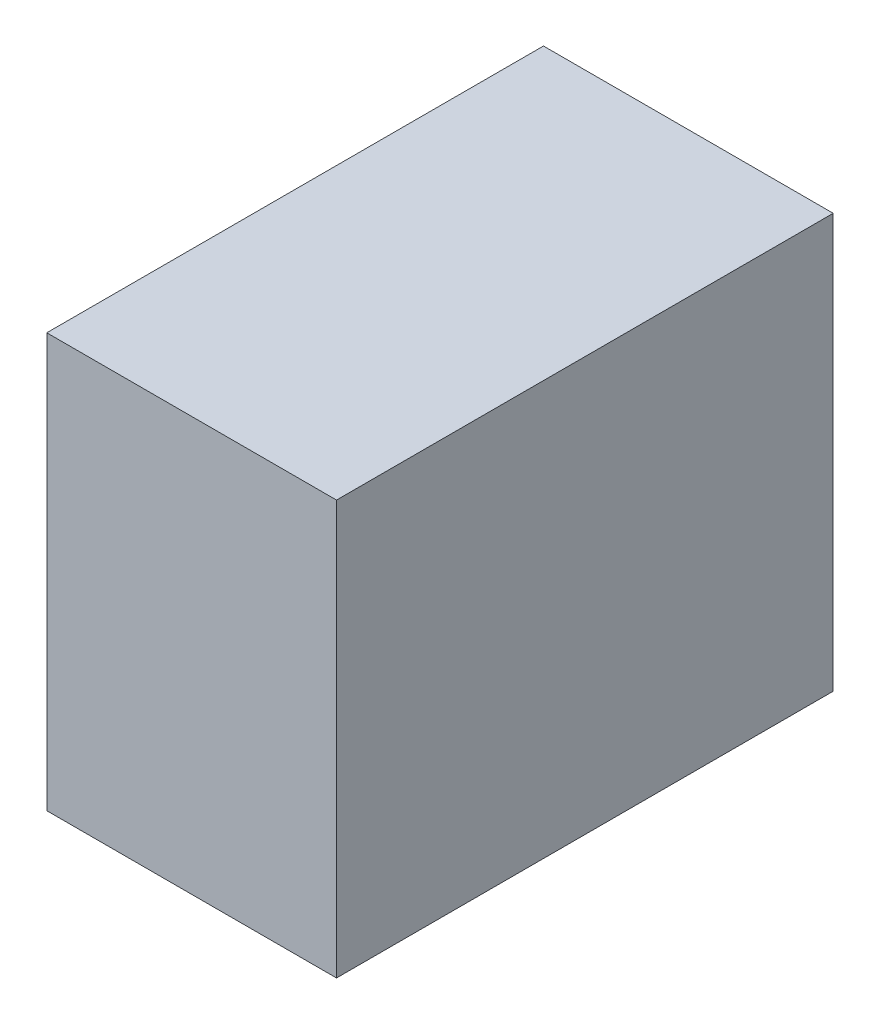
SolidWorks part; units mm, degrees
ref_plane "Front Plane" through (0, 0, 0) normal (0, 0, 1) x (1, 0, 0)
ref_plane "Top Plane" through (0, 0, 0) normal (0, 1, 0) x (1, 0, 0)
ref_plane "Right Plane" through (0, 0, 0) normal (1, 0, 0) x (0, 0, -1)
sketch "Sketch1" plane through (0, 0, 0) normal (0, 0, 1) x (1, 0, 0)
  line L1 (88.9, -127) -> (-88.9, -127)
  line L2 (88.9, -127) -> (88.9, 127)
  line L3 (88.9, 127) -> (-88.9, 127)
  line L4 (-88.9, -127) -> (-88.9, 127)
  line L5 (88.9, -127) -> (-88.9, 127) construction
  line L6 (88.9, 127) -> (-88.9, -127) construction
  point P0 (0, 0)
  dimension "D1" = 254
  dimension "D2" = 177.8
extrude "Boss-Extrude1" add sketch "Sketch1" along normal blind 304.8
